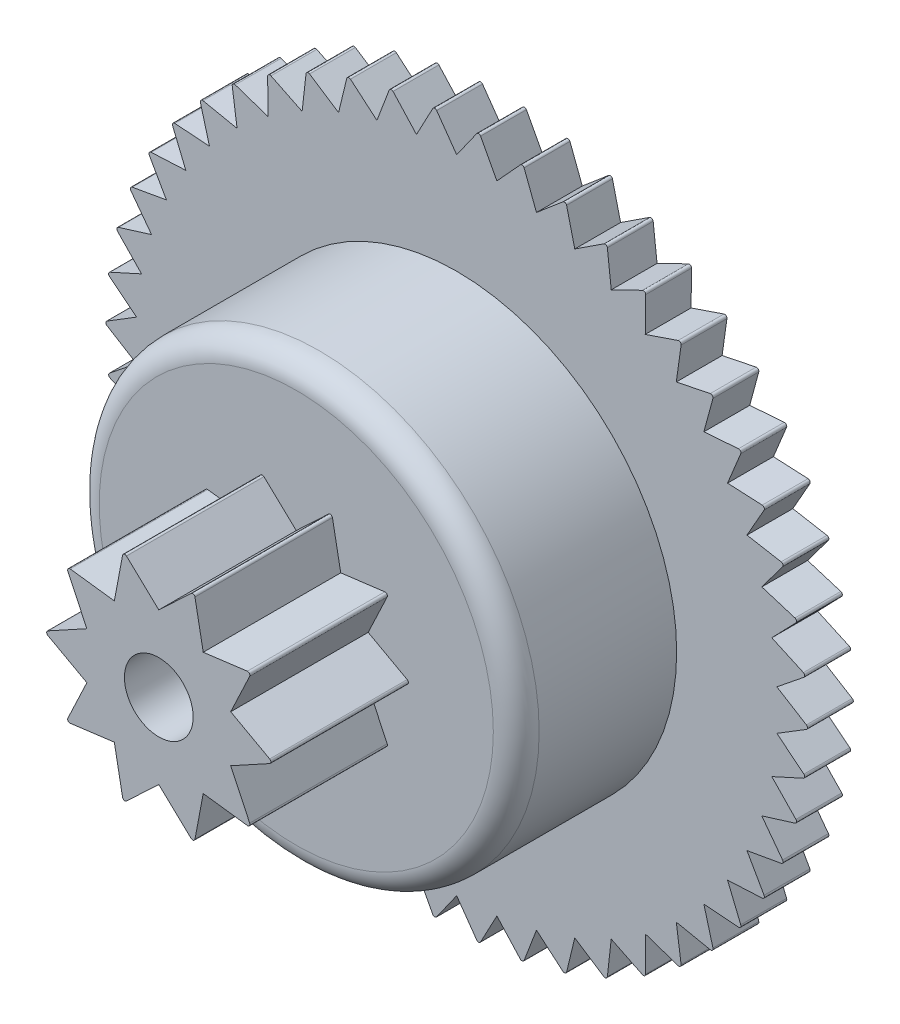
SolidWorks part; units mm, degrees
ref_plane "前基準面" through (0, 0, 0) normal (0, 0, 1) x (1, 0, 0)
ref_plane "上基準面" through (0, 0, 0) normal (0, 1, 0) x (1, 0, 0)
ref_plane "右基準面" through (0, 0, 0) normal (1, 0, 0) x (0, 0, -1)
sketch "草圖1" plane through (0, 0, 0) normal (0, 0, 1) x (1, 0, 0)
  circle A0 centre (0, 0) radius 7.7
  dimension "D1" = 15.4
extrude "伸長1" add sketch "草圖1" along normal blind 1
sketch "草圖2" plane through (0, 0, 1) normal (0, 0, 1) x (1, 0, 0)
  circle A0 centre (0, 0) radius 4.8
  dimension "D1" = 9.6
extrude "伸長2" add sketch "草圖2" along normal blind 3.5
sketch "草圖3" plane through (0, 0, 4.5) normal (0, 0, 1) x (1, 0, 0)
  circle A0 centre (0, 0) radius 2.5
  dimension "D1" = 5
extrude "伸長3" add sketch "草圖3" along normal blind 3
sketch "草圖4" plane through (0, 0, 1) normal (0, 0, 1) x (1, 0, 0)
  line L0 (0, 0) -> (0, 7.7) construction
  line L1 (0, 0) -> (0.9651, 7.6393) construction
  line L2 (0, 0) -> (0.4835, 7.6848) construction
  line L3 (0, 7) -> (0.4367, 7.6185)
  line L4 (0.5216, 7.6131) -> (0.8773, 6.9448)
  line L5 (1.4717, 7.4877) -> (1.7408, 6.7801)
  line L6 (0.8773, 6.9448) -> (1.3881, 7.5037)
  line L7 (2.3986, 7.2442) -> (2.5769, 6.5084)
  line L8 (1.7408, 6.7801) -> (2.3176, 7.2705)
  line L9 (3.2876, 6.8865) -> (3.3723, 6.1341)
  line L10 (2.5769, 6.5084) -> (3.2105, 6.9227)
  line L11 (4.1248, 6.4201) -> (4.1145, 5.6631)
  line L12 (3.3723, 6.1341) -> (4.0529, 6.4658)
  line L13 (4.8969, 5.8525) -> (4.7918, 5.1028)
  line L14 (4.1145, 5.6631) -> (4.8313, 5.9068)
  line L15 (5.5918, 5.1926) -> (5.3936, 4.462)
  line L16 (4.7918, 5.1028) -> (5.5335, 5.2547)
  line L17 (6.1985, 4.4509) -> (5.9103, 3.7508)
  line L18 (5.3936, 4.462) -> (6.1485, 4.5197)
  line L19 (6.7075, 3.6389) -> (6.3338, 2.9805)
  line L20 (5.9103, 3.7508) -> (6.6665, 3.7135)
  line L21 (7.1107, 2.7695) -> (6.6574, 2.1631)
  line L22 (6.3338, 2.9805) -> (7.0793, 2.8487)
  line L23 (7.4017, 1.8565) -> (6.876, 1.3117)
  line L24 (6.6574, 2.1631) -> (7.3805, 1.939)
  line L25 (7.576, 0.9142) -> (6.9862, 0.4395)
  line L26 (6.876, 1.3117) -> (7.5653, 0.9986)
  line L27 (7.6309, -0.0426) -> (6.9862, -0.4395)
  line L28 (6.9862, 0.4395) -> (7.6309, 0.0426)
  line L29 (7.5653, -0.9986) -> (6.876, -1.3117)
  line L30 (6.9862, -0.4395) -> (7.576, -0.9142)
  line L31 (7.3805, -1.939) -> (6.6574, -2.1631)
  line L32 (6.876, -1.3117) -> (7.4017, -1.8565)
  line L33 (7.0793, -2.8487) -> (6.3338, -2.9805)
  line L34 (6.6574, -2.1631) -> (7.1107, -2.7695)
  line L35 (6.6665, -3.7135) -> (5.9103, -3.7508)
  line L36 (6.3338, -2.9805) -> (6.7075, -3.6389)
  line L37 (6.1485, -4.5197) -> (5.3936, -4.462)
  line L38 (5.9103, -3.7508) -> (6.1985, -4.4509)
  line L39 (5.5335, -5.2547) -> (4.7918, -5.1028)
  line L40 (5.3936, -4.462) -> (5.5918, -5.1926)
  line L41 (4.8313, -5.9068) -> (4.1145, -5.6631)
  line L42 (4.7918, -5.1028) -> (4.8969, -5.8525)
  line L43 (4.0529, -6.4658) -> (3.3723, -6.1341)
  line L44 (4.1145, -5.6631) -> (4.1248, -6.4201)
  line L45 (3.2105, -6.9227) -> (2.5769, -6.5084)
  line L46 (3.3723, -6.1341) -> (3.2876, -6.8865)
  line L47 (2.3176, -7.2705) -> (1.7408, -6.7801)
  line L48 (2.5769, -6.5084) -> (2.3986, -7.2442)
  line L49 (1.3881, -7.5037) -> (0.8773, -6.9448)
  line L50 (1.7408, -6.7801) -> (1.4717, -7.4877)
  line L51 (0.4367, -7.6185) -> (0, -7)
  line L52 (0.8773, -6.9448) -> (0.5216, -7.6131)
  line L53 (-0.5216, -7.6131) -> (-0.8773, -6.9448)
  line L54 (0, -7) -> (-0.4367, -7.6185)
  line L55 (-1.4717, -7.4877) -> (-1.7408, -6.7801)
  line L56 (-0.8773, -6.9448) -> (-1.3881, -7.5037)
  line L57 (-2.3986, -7.2442) -> (-2.5769, -6.5084)
  line L58 (-1.7408, -6.7801) -> (-2.3176, -7.2705)
  line L59 (-3.2876, -6.8865) -> (-3.3723, -6.1341)
  line L60 (-2.5769, -6.5084) -> (-3.2105, -6.9227)
  line L61 (-4.1248, -6.4201) -> (-4.1145, -5.6631)
  line L62 (-3.3723, -6.1341) -> (-4.0529, -6.4658)
  line L63 (-4.8969, -5.8525) -> (-4.7918, -5.1028)
  line L64 (-4.1145, -5.6631) -> (-4.8313, -5.9068)
  line L65 (-5.5918, -5.1926) -> (-5.3936, -4.462)
  line L66 (-4.7918, -5.1028) -> (-5.5335, -5.2547)
  line L67 (-6.1985, -4.4509) -> (-5.9103, -3.7508)
  line L68 (-5.3936, -4.462) -> (-6.1485, -4.5197)
  line L69 (-6.7075, -3.6389) -> (-6.3338, -2.9805)
  line L70 (-5.9103, -3.7508) -> (-6.6665, -3.7135)
  line L71 (-7.1107, -2.7695) -> (-6.6574, -2.1631)
  line L72 (-6.3338, -2.9805) -> (-7.0793, -2.8487)
  line L73 (-7.4017, -1.8565) -> (-6.876, -1.3117)
  line L74 (-6.6574, -2.1631) -> (-7.3805, -1.939)
  line L75 (-7.576, -0.9142) -> (-6.9862, -0.4395)
  line L76 (-6.876, -1.3117) -> (-7.5653, -0.9986)
  line L77 (-7.6309, 0.0426) -> (-6.9862, 0.4395)
  line L78 (-6.9862, -0.4395) -> (-7.6309, -0.0426)
  line L79 (-7.5653, 0.9986) -> (-6.876, 1.3117)
  line L80 (-6.9862, 0.4395) -> (-7.576, 0.9142)
  line L81 (-7.3805, 1.939) -> (-6.6574, 2.1631)
  line L82 (-6.876, 1.3117) -> (-7.4017, 1.8565)
  line L83 (-7.0793, 2.8487) -> (-6.3338, 2.9805)
  line L84 (-6.6574, 2.1631) -> (-7.1107, 2.7695)
  line L85 (-6.6665, 3.7135) -> (-5.9103, 3.7508)
  line L86 (-6.3338, 2.9805) -> (-6.7075, 3.6389)
  line L87 (-6.1485, 4.5197) -> (-5.3936, 4.462)
  line L88 (-5.9103, 3.7508) -> (-6.1985, 4.4509)
  line L89 (-5.5335, 5.2547) -> (-4.7918, 5.1028)
  line L90 (-5.3936, 4.462) -> (-5.5918, 5.1926)
  line L91 (-4.8313, 5.9068) -> (-4.1145, 5.6631)
  line L92 (-4.7918, 5.1028) -> (-4.8969, 5.8525)
  line L93 (-4.0529, 6.4658) -> (-3.3723, 6.1341)
  line L94 (-4.1145, 5.6631) -> (-4.1248, 6.4201)
  line L95 (-3.2105, 6.9227) -> (-2.5769, 6.5084)
  line L96 (-3.3723, 6.1341) -> (-3.2876, 6.8865)
  line L97 (-2.3176, 7.2705) -> (-1.7408, 6.7801)
  line L98 (-2.5769, 6.5084) -> (-2.3986, 7.2442)
  line L99 (-1.3881, 7.5037) -> (-0.8773, 6.9448)
  line L100 (-1.7408, 6.7801) -> (-1.4717, 7.4877)
  line L101 (-0.4367, 7.6185) -> (0, 7)
  line L102 (-0.8773, 6.9448) -> (-0.5216, 7.6131)
  circle A0 centre (0, 0) radius 7.7 construction
  circle A1 centre (0, 0) radius 7 construction
  arc A2 (0.4367, 7.6185) -> (0.5216, 7.6131) centre (0.4775, 7.5896) cw
  arc A3 (1.3881, 7.5037) -> (1.4717, 7.4877) centre (1.425, 7.4699) cw
  arc A4 (2.3176, 7.2705) -> (2.3986, 7.2442) centre (2.35, 7.2324) cw
  arc A5 (3.2105, 6.9227) -> (3.2876, 6.8865) centre (3.2379, 6.8809) cw
  arc A6 (4.0529, 6.4658) -> (4.1248, 6.4201) centre (4.0748, 6.4208) cw
  arc A7 (4.8313, 5.9068) -> (4.8969, 5.8525) centre (4.8474, 5.8595) cw
  arc A8 (5.5335, 5.2547) -> (5.5918, 5.1926) centre (5.5435, 5.2057) cw
  arc A9 (6.1485, 4.5197) -> (6.1985, 4.4509) centre (6.1523, 4.4699) cw
  arc A10 (6.6665, 3.7135) -> (6.7075, 3.6389) centre (6.664, 3.6636) cw
  arc A11 (7.0793, 2.8487) -> (7.1107, 2.7695) centre (7.0706, 2.7995) cw
  arc A12 (7.3805, 1.939) -> (7.4017, 1.8565) centre (7.3657, 1.8912) cw
  arc A13 (7.5653, 0.9986) -> (7.576, 0.9142) centre (7.5447, 0.9531) cw
  arc A14 (7.6309, 0.0426) -> (7.6309, -0.0426) centre (7.6046, 0) cw
  arc A15 (7.576, -0.9142) -> (7.5653, -0.9986) centre (7.5447, -0.9531) cw
  arc A16 (7.4017, -1.8565) -> (7.3805, -1.939) centre (7.3657, -1.8912) cw
  arc A17 (7.1107, -2.7695) -> (7.0793, -2.8487) centre (7.0706, -2.7995) cw
  arc A18 (6.7075, -3.6389) -> (6.6665, -3.7135) centre (6.664, -3.6636) cw
  arc A19 (6.1985, -4.4509) -> (6.1485, -4.5197) centre (6.1523, -4.4699) cw
  arc A20 (5.5918, -5.1926) -> (5.5335, -5.2547) centre (5.5435, -5.2057) cw
  arc A21 (4.8969, -5.8525) -> (4.8313, -5.9068) centre (4.8474, -5.8595) cw
  arc A22 (4.1248, -6.4201) -> (4.0529, -6.4658) centre (4.0748, -6.4208) cw
  arc A23 (3.2876, -6.8865) -> (3.2105, -6.9227) centre (3.2379, -6.8809) cw
  arc A24 (2.3986, -7.2442) -> (2.3176, -7.2705) centre (2.35, -7.2324) cw
  arc A25 (1.4717, -7.4877) -> (1.3881, -7.5037) centre (1.425, -7.4699) cw
  arc A26 (0.5216, -7.6131) -> (0.4367, -7.6185) centre (0.4775, -7.5896) cw
  arc A27 (-0.4367, -7.6185) -> (-0.5216, -7.6131) centre (-0.4775, -7.5896) cw
  arc A28 (-1.3881, -7.5037) -> (-1.4717, -7.4877) centre (-1.425, -7.4699) cw
  arc A29 (-2.3176, -7.2705) -> (-2.3986, -7.2442) centre (-2.35, -7.2324) cw
  arc A30 (-3.2105, -6.9227) -> (-3.2876, -6.8865) centre (-3.2379, -6.8809) cw
  arc A31 (-4.0529, -6.4658) -> (-4.1248, -6.4201) centre (-4.0748, -6.4208) cw
  arc A32 (-4.8313, -5.9068) -> (-4.8969, -5.8525) centre (-4.8474, -5.8595) cw
  arc A33 (-5.5335, -5.2547) -> (-5.5918, -5.1926) centre (-5.5435, -5.2057) cw
  arc A34 (-6.1485, -4.5197) -> (-6.1985, -4.4509) centre (-6.1523, -4.4699) cw
  arc A35 (-6.6665, -3.7135) -> (-6.7075, -3.6389) centre (-6.664, -3.6636) cw
  arc A36 (-7.0793, -2.8487) -> (-7.1107, -2.7695) centre (-7.0706, -2.7995) cw
  arc A37 (-7.3805, -1.939) -> (-7.4017, -1.8565) centre (-7.3657, -1.8912) cw
  arc A38 (-7.5653, -0.9986) -> (-7.576, -0.9142) centre (-7.5447, -0.9531) cw
  arc A39 (-7.6309, -0.0426) -> (-7.6309, 0.0426) centre (-7.6046, 0) cw
  arc A40 (-7.576, 0.9142) -> (-7.5653, 0.9986) centre (-7.5447, 0.9531) cw
  arc A41 (-7.4017, 1.8565) -> (-7.3805, 1.939) centre (-7.3657, 1.8912) cw
  arc A42 (-7.1107, 2.7695) -> (-7.0793, 2.8487) centre (-7.0706, 2.7995) cw
  arc A43 (-6.7075, 3.6389) -> (-6.6665, 3.7135) centre (-6.664, 3.6636) cw
  arc A44 (-6.1985, 4.4509) -> (-6.1485, 4.5197) centre (-6.1523, 4.4699) cw
  arc A45 (-5.5918, 5.1926) -> (-5.5335, 5.2547) centre (-5.5435, 5.2057) cw
  arc A46 (-4.8969, 5.8525) -> (-4.8313, 5.9068) centre (-4.8474, 5.8595) cw
  arc A47 (-4.1248, 6.4201) -> (-4.0529, 6.4658) centre (-4.0748, 6.4208) cw
  arc A48 (-3.2876, 6.8865) -> (-3.2105, 6.9227) centre (-3.2379, 6.8809) cw
  arc A49 (-2.3986, 7.2442) -> (-2.3176, 7.2705) centre (-2.35, 7.2324) cw
  arc A50 (-1.4717, 7.4877) -> (-1.3881, 7.5037) centre (-1.425, 7.4699) cw
  arc A51 (-0.5216, 7.6131) -> (-0.4367, 7.6185) centre (-0.4775, 7.5896) cw
  dimension "D1" = 14
  dimension "D4" = 0.05
  dimension "D2" = 7.2
  dimension "D3" = 3.6
sketch "草圖5" plane through (0, 0, 1) normal (0, 0, 1) x (1, 0, 0)
  circle A0 centre (0, 0) radius 7.7 construction
  circle A1 centre (0, 0) radius 7.7
extrude "伸長7" cut sketch "草圖4" against normal blind 3 flip side to cut
sketch "草圖6" plane through (0, 0, 7.5) normal (0, 0, 1) x (1, 0, 0)
  line L0 (0, 0) -> (0, 2.5) construction
  line L1 (0, 0) -> (1.4695, 2.0225) construction
  line L2 (0, 0) -> (0.7725, 2.3776) construction
  line L3 (0, 1.65) -> (0.7061, 2.3151)
  line L4 (0.7895, 2.288) -> (0.9698, 1.3349)
  line L5 (0.9698, 1.3349) -> (1.932, 1.4579)
  line L6 (1.9836, 1.3869) -> (1.5692, 0.5099)
  line L7 (1.5692, 0.5099) -> (2.42, 0.0439)
  line L8 (2.42, -0.0439) -> (1.5692, -0.5099)
  line L9 (1.5692, -0.5099) -> (1.9836, -1.3869)
  line L10 (1.932, -1.4579) -> (0.9698, -1.3349)
  line L11 (0.9698, -1.3349) -> (0.7895, -2.288)
  line L12 (0.7061, -2.3151) -> (0, -1.65)
  line L13 (0, -1.65) -> (-0.7061, -2.3151)
  line L14 (-0.7895, -2.288) -> (-0.9698, -1.3349)
  line L15 (-0.9698, -1.3349) -> (-1.932, -1.4579)
  line L16 (-1.9836, -1.3869) -> (-1.5692, -0.5099)
  line L17 (-1.5692, -0.5099) -> (-2.42, -0.0439)
  line L18 (-2.42, 0.0439) -> (-1.5692, 0.5099)
  line L19 (-1.5692, 0.5099) -> (-1.9836, 1.3869)
  line L20 (-1.932, 1.4579) -> (-0.9698, 1.3349)
  line L21 (-0.9698, 1.3349) -> (-0.7895, 2.288)
  line L22 (-0.7061, 2.3151) -> (0, 1.65)
  circle A0 centre (0, 0) radius 1.65 construction
  circle A1 centre (0, 0) radius 2.5 construction
  circle A2 centre (0, 0) radius 2.5 construction
  arc A3 (0.7061, 2.3151) -> (0.7895, 2.288) centre (0.7404, 2.2787) cw
  arc A4 (1.932, 1.4579) -> (1.9836, 1.3869) centre (1.9383, 1.4083) cw
  arc A5 (2.42, 0.0439) -> (2.42, -0.0439) centre (2.3959, 0) cw
  arc A6 (1.9836, -1.3869) -> (1.932, -1.4579) centre (1.9383, -1.4083) cw
  arc A7 (0.7895, -2.288) -> (0.7061, -2.3151) centre (0.7404, -2.2787) cw
  arc A8 (-0.7061, -2.3151) -> (-0.7895, -2.288) centre (-0.7404, -2.2787) cw
  arc A9 (-1.932, -1.4579) -> (-1.9836, -1.3869) centre (-1.9383, -1.4083) cw
  arc A10 (-2.42, -0.0439) -> (-2.42, 0.0439) centre (-2.3959, 0) cw
  arc A11 (-1.9836, 1.3869) -> (-1.932, 1.4579) centre (-1.9383, 1.4083) cw
  arc A12 (-0.7895, 2.288) -> (-0.7061, 2.3151) centre (-0.7404, 2.2787) cw
  dimension "D3" = 3.3
  dimension "D4" = 0.05
  dimension "D1" = 36
  dimension "D2" = 18
extrude "伸長8" cut sketch "草圖6" against normal blind 3 flip side to cut
sketch "草圖7" plane through (0, 0, 7.5) normal (0, 0, 1) x (1, 0, 0)
  circle A0 centre (0, 0) radius 0.75
  dimension "D1" = 1.5
extrude "伸長9" cut sketch "草圖7" against normal through all
sketch "草圖8" plane through (0, 0, 0) normal (0, 0, -1) x (-1, 0, 0)
  circle A0 centre (0, 0) radius 3.75
  dimension "D1" = 7.5
extrude "伸長10" cut sketch "草圖8" against normal blind 3.5
fillet "圓角1" radius 0.5 1 edges at (4.8, 0, 4.5)
fillet "圓角2" radius 0.5 1 edges at (-3.75, 0, 3.5)
